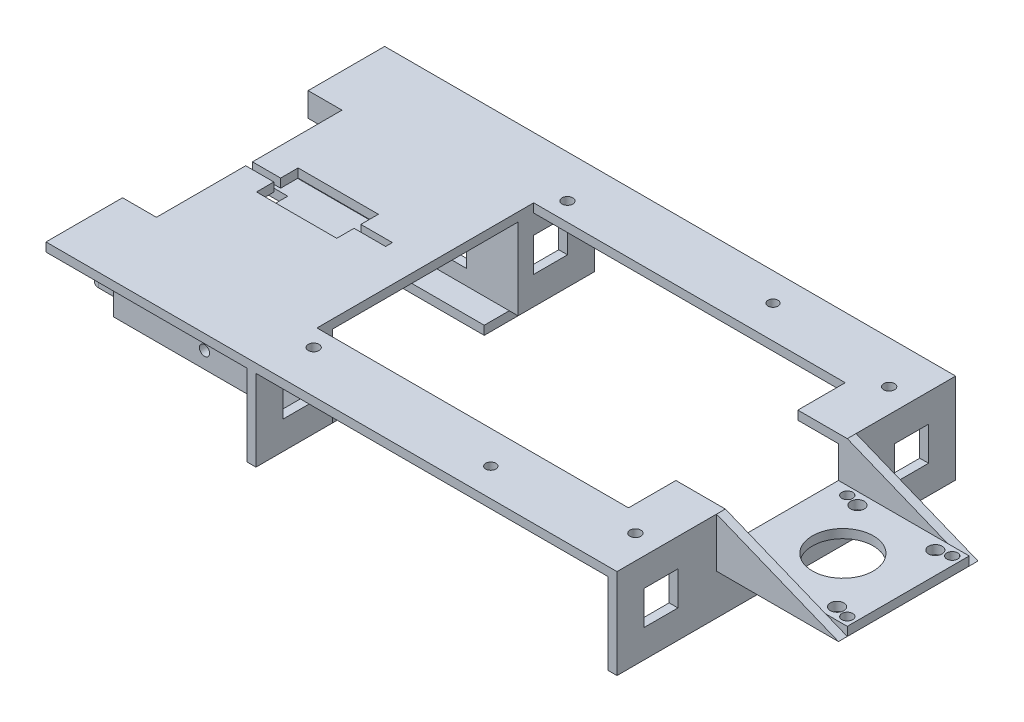
SolidWorks part; units mm, degrees
ref_plane "前视基准面" through (0, 0, 0) normal (0, 0, 1) x (1, 0, 0)
ref_plane "上视基准面" through (0, 0, 0) normal (0, 1, 0) x (1, 0, 0)
ref_plane "右视基准面" through (0, 0, 0) normal (1, 0, 0) x (0, 0, -1)
sketch "草图1" plane through (0, 0, 0) normal (0, 1, 0) x (1, 0, 0)
  line L0 (0, 0) -> (168.1938, 0) construction
  line L1 (0, 0) -> (0, 68.5187) construction
  line L2 (0, 50) -> (-52, 50)
  line L3 (-52, 50) -> (52, 50)
  line L5 (-52, -50) -> (52, -50)
  line L7 (0, 50) -> (52, 50)
  line L8 (52, 50) -> (52, -50)
  line L9 (-52, -50) -> (-52, 50)
  dimension "D1" = 100
  dimension "D3" = 52
  dimension "D4" = 52
extrude "凸台-拉伸1" add sketch "草图1" along normal blind 2.6 contours L9 L5 L8 L3 L2
ref_plane "基准面1" through (-52, 0, 0) normal (-1, 0, 0) x (0, 0, 1)
sketch "草图2" plane through (-52, 0, 0) normal (-1, 0, 0) x (0, 0, 1)
  line L0 (0, 0) -> (60.8879, 0) construction
  line L1 (0, 0) -> (0, 52.5684) construction
  line L4 (-50, 0) -> (50, 0)
  line L5 (-50, 0) -> (-50, 24)
  line L6 (-50, 24) -> (50, 24)
  line L7 (50, 0) -> (50, 24)
  dimension "D1" = 100
  dimension "D2" = 24
extrude "凸台-拉伸2" add sketch "草图2" along normal blind 2.6
ref_plane "基准面2" through (52, 0, 0) normal (1, 0, 0) x (0, 0, -1)
sketch "草图4" plane through (52, 0, 0) normal (1, 0, 0) x (0, 0, -1)
  line L0 (0, 0) -> (83.3328, 0) construction
  line L1 (0, 79.0959) -> (0, 0) construction
  line L3 (-50, 0) -> (50, 0)
  line L4 (-50, 0) -> (-50, 24)
  line L5 (-50, 24) -> (50, 24)
  line L6 (50, 0) -> (50, 24)
  dimension "D1" = 100
  dimension "D2" = 24
extrude "凸台-拉伸3" add sketch "草图4" along normal blind 2.6
ref_plane "基准面3" through (0, 24, 0) normal (0, 1, 0) x (1, 0, 0)
sketch "草图5" plane through (0, 24, 0) normal (0, 1, 0) x (1, 0, 0)
  line L0 (-54.6, 0) -> (-54.6, -62.7888) construction
  line L2 (-54.6, 0) -> (-103.1828, 0) construction
  line L3 (-52, 50) -> (-114, 50)
  line L4 (-52, 50) -> (-52, -50)
  line L5 (-52, -50) -> (-114, -50)
  line L6 (-114, 50) -> (-114, -50)
  dimension "D1" = 62
  dimension "D2" = 100
extrude "凸台-拉伸5" add sketch "草图5" along normal blind 2.6
ref_plane "基准面4" through (0, 24, 0) normal (0, 1, 0) x (1, 0, 0)
sketch "草图7" plane through (0, 24, 0) normal (0, 1, 0) x (1, 0, 0)
  line L0 (54.6, 0) -> (137.447, 0) construction
  line L2 (54.6, 0) -> (54.6, 43.4871) construction
  line L4 (52, -50) -> (114, -50)
  line L5 (52, -50) -> (52, 50)
  line L6 (52, 50) -> (114, 50)
  line L7 (114, -50) -> (114, 50)
  dimension "D1" = 62
  dimension "D2" = 100
extrude "凸台-拉伸6" add sketch "草图7" along normal blind 2.6
sketch "草图8" plane through (0, 24, 0) normal (0, 1, 0) x (1, 0, 0)
  line L13 (-54.6, 50) -> (-114, 50) construction
  line L14 (-114, 30) -> (-54.6, 30)
  line L15 (-114, 30) -> (-114, -30)
  line L16 (-114, -30) -> (-54.6, -30)
  line L17 (-54.6, 30) -> (-54.6, -30)
  line L18 (-114, -50) -> (-54.6, -50) construction
  line L19 (-54.6, -50) -> (-54.6, 50) construction
  line L20 (-114, 50) -> (-114, -50) construction
  dimension "D1" = 20
  dimension "D2" = 20
  dimension "D3" = 0
  dimension "D4" = 0
extrude "切除-拉伸1" cut sketch "草图8" along normal blind 2.6
sketch "草图9" plane through (0, 24, 0) normal (0, -1, 0) x (1, 0, 0)
  line L0 (54.6, 50) -> (114, 50) construction
  line L1 (54.6, 30) -> (114, 30)
  line L2 (54.6, 30) -> (54.6, -30)
  line L3 (54.6, -30) -> (114, -30)
  line L4 (114, 30) -> (114, -30)
  line L5 (114, -50) -> (54.6, -50) construction
  line L6 (54.6, -50) -> (54.6, 50) construction
  line L7 (114, 50) -> (114, -50) construction
  dimension "D1" = 20
  dimension "D2" = 20
  dimension "D3" = 0
  dimension "D4" = 0
extrude "切除-拉伸2" cut sketch "草图9" against normal blind 2.6
ref_plane "基准面6" through (0, 0, 30) normal (0, 0, -1) x (-1, 0, 0)
sketch "草图11" plane through (0, 0, 30) normal (0, 0, -1) x (-1, 0, 0)
  line L2 (-114, 26.6) -> (-54.6, 26.6)
  line L3 (-114, 26.6) -> (-114, 0)
  line L4 (-114, 0) -> (-54.6, 0)
  line L5 (-54.6, 26.6) -> (-54.6, 0)
extrude "凸台-拉伸7" add sketch "草图11" along normal blind 2.6
ref_plane "基准面7" through (0, 0, -30) normal (0, 0, 1) x (1, 0, 0)
sketch "草图12" plane through (0, 0, -30) normal (0, 0, 1) x (1, 0, 0)
  line L2 (54.6, 26.6) -> (114, 26.6)
  line L3 (54.6, 26.6) -> (54.6, 0)
  line L4 (54.6, 0) -> (114, 0)
  line L5 (114, 26.6) -> (114, 0)
extrude "凸台-拉伸8" add sketch "草图12" along normal blind 2.6
ref_plane "基准面8" through (0, 0, -30) normal (0, 0, 1) x (1, 0, 0)
sketch "草图14" plane through (0, 0, -30) normal (0, 0, 1) x (1, 0, 0)
  line L1 (-54.6, 26.6) -> (-114, 26.6)
  line L2 (-54.6, 26.6) -> (-54.6, 0)
  line L3 (-54.6, 0) -> (-114, 0)
  line L4 (-114, 26.6) -> (-114, 0)
extrude "凸台-拉伸9" add sketch "草图14" along normal blind 2.6
ref_plane "基准面9" through (0, 0, 30) normal (0, 0, -1) x (-1, 0, 0)
sketch "草图15" plane through (0, 0, 30) normal (0, 0, -1) x (-1, 0, 0)
  line L2 (54.6, 26.6) -> (114, 26.6)
  line L3 (54.6, 26.6) -> (54.6, 0)
  line L4 (54.6, 0) -> (114, 0)
  line L5 (114, 26.6) -> (114, 0)
extrude "凸台-拉伸10" add sketch "草图15" along normal blind 2.6
sketch "草图16" plane through (0, 2.6, 0) normal (0, 1, 0) x (1, 0, 0)
  line L0 (0, 0) -> (88.5453, 0) construction
  line L1 (0, 0) -> (0, 69.8905) construction
  circle A0 centre (-47.5, 37.465) radius 1.6
  circle A4 centre (47.5, 37.465) radius 1.6
  circle A5 centre (-47.5, -37.465) radius 1.6
  circle A6 centre (47.5, -37.465) radius 1.6
  dimension "D1" = 3.2
  dimension "D2" = 47.5
  dimension "D3" = 37.465
extrude "切除-拉伸3" cut sketch "草图16" against normal through all
sketch "草图17" plane through (0, 2.6, 0) normal (0, 1, 0) x (1, 0, 0)
  line L0 (0, 0) -> (0, -106.8297) construction
  line L1 (-40, 32) -> (40, 32)
  line L2 (-40, 32) -> (-40, -32)
  line L3 (-40, -32) -> (40, -32)
  line L4 (40, 32) -> (40, -32)
  line L5 (0, 0) -> (46.3374, 0) construction
  dimension "D1" = 80
  dimension "D2" = 64
extrude "切除-拉伸4" cut sketch "草图17" against normal through all contours L2 L1 L4 L3
sketch "草图19" plane through (0, 26.6, 0) normal (0, 1, 0) x (1, 0, 0)
sketch "草图21" plane through (0, 0, 0) normal (0, -1, 0) x (1, 0, 0)
  line L1 (-54.6, 27.4) -> (-114, 27.4)
  line L2 (-54.6, 27.4) -> (-54.6, -27.4)
  line L3 (-54.6, -27.4) -> (-114, -27.4)
  line L4 (-114, 27.4) -> (-114, -27.4)
extrude "凸台-拉伸11" add sketch "草图21" against normal blind 2.6
sketch "草图22" plane through (0, 2.6, 0) normal (0, 1, 0) x (1, 0, 0)
  line L0 (-114, -27.4) -> (-114, 27.4) construction
  line L1 (-114, 0) -> (-47.7388, 0) construction
  circle A0 centre (-109, 18) radius 1.6
  circle A1 centre (-109, 0) radius 1.6
  circle A2 centre (-109, -18) radius 1.6
  dimension "D1" = 3.2
  dimension "D3" = 3.2
  dimension "D2" = 5
  dimension "D4" = 18
extrude "切除-拉伸5" cut sketch "草图22" against normal blind 2.6
sketch "草图23" plane through (0, 26.6, 0) normal (0, 1, 0) x (1, 0, 0)
  line L1 (-114, 27.4) -> (-54.6, 27.4)
  line L2 (-114, 27.4) -> (-114, -27.4)
  line L3 (-114, -27.4) -> (-54.6, -27.4)
  line L4 (-54.6, 27.4) -> (-54.6, -27.4)
extrude "凸台-拉伸13" add sketch "草图23" against normal blind 2.6
sketch "草图24" plane through (0, 26.6, 0) normal (0, 1, 0) x (1, 0, 0)
  line L2 (-114, 0) -> (-114, 69.485) construction
  line L3 (-114, 27.4) -> (-104, 27.4)
  line L4 (-114, 27.4) -> (-114, -27.4)
  line L5 (-114, -27.4) -> (-104, -27.4)
  line L6 (-104, 27.4) -> (-104, 0.9702)
  line L7 (-94.7, 6.15) -> (-72, 6.15)
  line L8 (-94.7, 6.15) -> (-94.7, 0.9702)
  line L9 (-94.7, -6.15) -> (-72, -6.15)
  line L10 (-72, 6.15) -> (-72, 0.9702)
  line L11 (-52, -50) -> (-52, 50) construction
  line L12 (-104, -1.0298) -> (-104, -27.4)
  line L13 (-104, 0.9702) -> (-94.7, 0.9702)
  line L15 (-104, -1.0298) -> (-94.7, -1.0298)
  line L17 (-72, 0.9702) -> (-62.7, 0.9702)
  line L19 (-72, -1.0298) -> (-62.7, -1.0298)
  line L20 (-62.7, 0.9702) -> (-62.7, -1.0298)
  line L21 (-94.7, -1.0298) -> (-94.7, -6.15)
  line L22 (-72, -1.0298) -> (-72, -6.15)
  line L23 (-62.7, 0) -> (11.6044, 0) construction
  dimension "D1" = 54.8
  dimension "D2" = 0
  dimension "D4" = 22.7
  dimension "D5" = 12.3
  dimension "D6" = 20
  dimension "D7" = 2
  dimension "D8" = 9.3
  dimension "D9" = 9.3
extrude "切除-拉伸8" cut sketch "草图24" against normal blind 2.6 contours L7 L10 L17 L20 L19 L22 L9 L21 L15 L12 L5 L4 L3 L6 L13 L8
sketch "草图25" plane through (-54.6, 0, 0) normal (-1, 0, 0) x (0, 0, 1)
  line L2 (-27.4, 24) -> (27.4, 24)
  line L3 (-27.4, 24) -> (-27.4, 2.6)
  line L4 (-27.4, 2.6) -> (27.4, 2.6)
  line L5 (27.4, 24) -> (27.4, 2.6)
extrude "切除-拉伸9" cut sketch "草图25" against normal blind 2.6
sketch "草图28" plane through (0, 0, 30) normal (0, 0, 1) x (1, 0, 0)
  line L0 (-54.6, 24) -> (-54.6, 0) construction
  line L1 (-54.6, 12) -> (-123.8904, 12) construction
  circle A0 centre (-87.2, 20.75) radius 1.5
  circle A1 centre (-87.2, 3.25) radius 1.5
  dimension "D1" = 3
  dimension "D2" = 32.6
  dimension "D3" = 17.5
extrude "切除-拉伸11" cut sketch "草图28" against normal up to surface and the other way through all up to face at (-84.3, 12, -30)
sketch "草图31" plane through (0, 2.6, 0) normal (0, 1, 0) x (1, 0, 0)
  line L0 (-88.5519, -27.4) -> (-114, -27.4) construction
  line L1 (-52, 27.4) -> (-93.9958, 27.4)
  line L2 (-52, 27.4) -> (-52, -27.4)
  line L3 (-52, -27.4) -> (-93.9958, -27.4)
  line L4 (-93.9958, 27.4) -> (-93.9958, -27.4)
extrude "切除-拉伸14" cut sketch "草图31" against normal blind 2.6
sketch "草图32" plane through (0, 0, 30) normal (0, 0, 1) x (1, 0, 0)
  line L1 (54.6, 24) -> (114, 24)
  line L2 (54.6, 24) -> (54.6, 0)
  line L3 (54.6, 0) -> (114, 0)
  line L4 (114, 24) -> (114, 0)
extrude "切除-拉伸15" cut sketch "草图32" against normal blind 70.6
sketch "草图33" plane through (0, 2.6, 0) normal (0, 1, 0) x (1, 0, 0)
  line L1 (-52, 50) -> (52, 50)
  line L2 (-52, 50) -> (-52, -50)
  line L3 (-52, -50) -> (52, -50)
  line L4 (52, 50) -> (52, -50)
extrude "切除-拉伸16" cut sketch "草图33" against normal blind 2.6
sketch "草图34" plane through (0, 0, 0) normal (0, -1, 0) x (1, 0, 0)
  line L0 (52, 50) -> (52, -50) construction
  line L1 (-52, 50) -> (52, 50)
  line L2 (-52, 50) -> (-52, -49.6726)
  line L3 (-52, -49.6726) -> (52, -49.6726)
  line L4 (52, 50) -> (52, -49.6726)
extrude "凸台-拉伸14" add sketch "草图34" against normal blind 2.6
sketch "草图35" plane through (0, 2.6, 0) normal (0, 1, 0) x (1, 0, 0)
  line L0 (0, 0) -> (174.9155, 0) construction
  line L1 (0, 0) -> (0, 73.4475) construction
  line L4 (-42, 24) -> (12, 24) construction
  line L5 (-42, 24) -> (-42, -24) construction
  line L6 (-42, -24) -> (12, -24) construction
  line L7 (12, 24) -> (12, -24) construction
  line L8 (-52, 27.4) -> (-52, 49.6726) construction
  circle A0 centre (-39.5, 21.5) radius 1.6
  circle A2 centre (9.5, 21.5) radius 1.6
  circle A3 centre (9.5, -21.5) radius 1.6
  circle A4 centre (-39.5, -21.5) radius 1.6
  dimension "D4" = 3.2
  dimension "D5" = 2.5
  dimension "D6" = 2.5
  dimension "D7" = 3.2
  dimension "D8" = 2.5
  dimension "D9" = 2.5
  dimension "D1" = 54
  dimension "D2" = 48
  dimension "D3" = 10
extrude "切除-拉伸24" cut sketch "草图35" against normal blind 2.6
sketch "草图36" plane through (0, 26.6, 0) normal (0, 1, 0) x (1, 0, 0)
  line L0 (52, -50) -> (114, -50) construction
  line L1 (114, 50) -> (54.6, 50)
  line L2 (114, 50) -> (114, -50)
  line L3 (114, -50) -> (54.6, -50)
  line L4 (54.6, 50) -> (54.6, -50)
extrude "切除-拉伸25" cut sketch "草图36" against normal blind 2.6
sketch "草图37" plane through (54.6, 0, 0) normal (1, 0, 0) x (0, 0, -1)
  line L0 (0, 0) -> (0, 48.9545) construction
  line L1 (-50, 0) -> (50, 0) construction
  line L2 (50, 13.3) -> (-60.8276, 13.3) construction
  line L4 (-18, 14.6) -> (18, 14.6)
  line L5 (-18, 14.6) -> (-18, 12)
  line L6 (-18, 12) -> (18, 12)
  line L7 (18, 14.6) -> (18, 12)
  dimension "D1" = 2.6
  dimension "D2" = 36
  dimension "D3" = 12
extrude "凸台-拉伸17" add sketch "草图37" along normal blind 36
sketch "草图41" plane through (54.6, 0, 0) normal (1, 0, 0) x (0, 0, -1)
  line L0 (-50, 26.6) -> (50, 26.6) construction
  line L1 (-18, 14.6) -> (18, 14.6)
  line L2 (-18, 14.6) -> (-18, 26.6)
  line L3 (-18, 26.6) -> (18, 26.6)
  line L4 (18, 14.6) -> (18, 26.6)
  dimension "D1" = 36
extrude "切除-拉伸27" cut sketch "草图41" against normal blind 2.6
sketch "草图42" plane through (0, 14.6, 0) normal (0, 1, 0) x (1, 0, 0)
  line L0 (90.6, 18) -> (54.6, 18) construction
  line L4 (90.6, 18) -> (90.6, -18) construction
  line L5 (90.6, 0) -> (52, 0) construction
  circle A0 centre (88.1, 15.5) radius 1.6
  circle A1 centre (88.1, -15.5) radius 1.6
  circle A2 centre (57.1, 15.5) radius 1.6
  circle A3 centre (57.1, -15.5) radius 1.6
  dimension "D1" = 3.2
  dimension "D2" = 2.5
  dimension "D3" = 2.5
  dimension "D4" = 2
extrude "切除-拉伸28" cut sketch "草图42" against normal blind 2.6
sketch "草图43" plane through (0, 14.6, 0) normal (0, 1, 0) x (1, 0, 0)
  line L0 (90.6, 0) -> (48.4873, 0) construction
  line L1 (90.6, 18) -> (90.6, -18) construction
  line L2 (57.1, 15.5) -> (88.1, 15.5)
  line L3 (72.6, 15.5) -> (72.6, -18) construction
  line L4 (90.6, -18) -> (54.6, -18) construction
  circle A0 centre (61.1, 14.5) radius 2
  circle A1 centre (84.1, 14.5) radius 2
  circle A2 centre (84.1, -14.5) radius 2
  circle A3 centre (61.1, -14.5) radius 2
  dimension "D1" = 4
  dimension "D3" = 11.5
  dimension "D4" = 14.5
extrude "切除-拉伸29" cut sketch "草图43" against normal blind 2.6 contours A0 | A1 | A3 | A2
sketch "草图44" plane through (0, 26.6, 0) normal (0, 1, 0) x (1, 0, 0)
  line L1 (-52, 49.6726) -> (52, 49.6726)
  line L2 (-52, 49.6726) -> (-52, -50)
  line L3 (-52, -50) -> (52, -50)
  line L4 (52, 49.6726) -> (52, -50)
extrude "凸台-拉伸18" add sketch "草图44" against normal blind 2.6
sketch "草图45" plane through (0, 26.6, 0) normal (0, 1, 0) x (1, 0, 0)
  line L0 (-61.404, 0) -> (112.1459, 0) construction
  line L1 (-50, 40) -> (50, 40) construction
  line L2 (-50, 40) -> (-50, -40) construction
  line L3 (-50, -40) -> (50, -40) construction
  line L4 (50, 40) -> (50, -40) construction
  line L5 (0, 0) -> (0, 74.2403) construction
  circle A0 centre (-47.5, -37.465) radius 1.6
  circle A1 centre (-47.5, 37.465) radius 1.6
  circle A2 centre (47.5, -37.465) radius 1.6
  circle A3 centre (47.5, 37.465) radius 1.6
  dimension "D1" = 3.2
  dimension "D2" = 2.535
  dimension "D3" = 2.5
extrude "切除-拉伸30" cut sketch "草图45" against normal blind 2.6
sketch "草图46" plane through (0, 26.6, 0) normal (0, 1, 0) x (1, 0, 0)
  line L0 (0, 0) -> (106.198, 0) construction
  line L1 (-40, 32) -> (40, 32)
  line L2 (-40, 32) -> (-40, -32)
  line L3 (-40, -32) -> (40, -32)
  line L4 (40, 32) -> (40, -32)
  line L5 (0, 0) -> (0, 58.9714) construction
  dimension "D1" = 80
  dimension "D2" = 64
extrude "切除-拉伸31" cut sketch "草图46" against normal blind 2.6 contours L2 L1 L4 L3
sketch "草图47" plane through (0, 2.6, 0) normal (0, 1, 0) x (1, 0, 0)
  line L0 (-40, 0) -> (22.2042, 0) construction
  line L3 (-15, 21.5) -> (-15, -18.6922) construction
  line L4 (-35, 15) -> (5, 15)
  line L5 (-35, 15) -> (-35, -15)
  line L6 (-35, -15) -> (5, -15)
  line L7 (5, 15) -> (5, -15)
  dimension "D1" = 40
  dimension "D2" = 30
extrude "切除-拉伸32" cut sketch "草图47" against normal blind 2.6 contours L5 L4 L7 L6
sketch "草图48" plane through (0, 26.6, 0) normal (0, 1, 0) x (1, 0, 0)
  line L1 (-40, 32) -> (-52, 32)
  line L2 (-40, 32) -> (-40, -32)
  line L3 (-40, -32) -> (-52, -32)
  line L4 (-52, 32) -> (-52, -32)
  dimension "D1" = 12
extrude "切除-拉伸33" cut sketch "草图48" against normal blind 2.6
sketch "草图49" plane through (0, 2.6, 0) normal (0, 1, 0) x (1, 0, 0)
  line L6 (-35, 15) -> (5, 15)
  line L7 (-35, 15) -> (-35, 35.5471)
  line L8 (-35, 35.5471) -> (5, 35.5471)
  line L9 (5, 15) -> (5, 35.5471)
  line L10 (-35, -15) -> (5, -15)
  line L11 (-35, -15) -> (-35, -35)
  line L12 (-35, -35) -> (5, -35)
  line L13 (5, -15) -> (5, -35)
  dimension "D1" = 20
extrude "切除-拉伸34" cut sketch "草图49" against normal blind 2.6 contours L11 L10 L13 L12
sketch "草图50" plane through (0, 2.6, 0) normal (0, 1, 0) x (1, 0, 0)
  line L1 (-35, 15) -> (4.9378, 15)
  line L2 (-35, 15) -> (-35, 35)
  line L3 (-35, 35) -> (4.9378, 35)
  line L4 (4.9378, 15) -> (4.9378, 35)
  dimension "D1" = 20
extrude "切除-拉伸35" cut sketch "草图50" against normal blind 2.6
sketch "草图51" plane through (0, 14.6, 0) normal (0, 1, 0) x (1, 0, 0)
  line L4 (52, 18) -> (90.6, -18) construction
  line L6 (90.6, 18) -> (52, -18) construction
  circle A1 centre (71.3, 0) radius 9
  dimension "D1" = 18
extrude "切除-拉伸36" cut sketch "草图51" against normal blind 2.6
sketch "草图52" plane through (0, 0, 30) normal (0, 0, 1) x (1, 0, 0)
  line L0 (-87.2, 20.75) -> (-87.2, 3.25) construction
  line L1 (-87.2, 12) -> (-58.053, 12) construction
  line L2 (-67.2, 4.5) -> (-82.2, 4.5)
  line L3 (-107.2, 19.5) -> (-92.2, 19.5)
  line L4 (-107.2, 19.5) -> (-107.2, 4.5)
  line L5 (-107.2, 4.5) -> (-92.2, 4.5)
  line L6 (-92.2, 19.5) -> (-92.2, 4.5)
  line L7 (-82.2, 19.5) -> (-82.2, 4.5)
  line L8 (-67.2, 19.5) -> (-82.2, 19.5)
  line L9 (-67.2, 19.5) -> (-67.2, 4.5)
  dimension "D1" = 15
  dimension "D2" = 15
  dimension "D3" = 5
extrude "切除-拉伸38" cut sketch "草图52" against normal up to surface (60 mm away) up to face at (-88.7, 20.75, -30)
sketch "草图55" plane through (52, 0, 0) normal (1, 0, 0) x (0, 0, -1)
  line L1 (-18, 26.6) -> (18, 26.6)
  line L2 (-18, 26.6) -> (-18, 24)
  line L3 (-18, 24) -> (18, 24)
  line L4 (18, 26.6) -> (18, 24)
extrude "切除-拉伸39" cut sketch "草图55" against normal up to surface (12 mm away) up to face at (40, 25.3, 0)
sketch "草图56" plane through (54.6, 0, 0) normal (1, 0, 0) x (0, 0, -1)
  line L0 (-50, 13.3) -> (50, 13.3) construction
  line L3 (0, 0) -> (0, 44.005) construction
  line L5 (-50, 26.6) -> (-50, 0) construction
  line L6 (-42, 18.3) -> (-32, 18.3)
  line L7 (-42, 18.3) -> (-42, 8.3)
  line L8 (-42, 8.3) -> (-32, 8.3)
  line L9 (-32, 18.3) -> (-32, 8.3)
  line L10 (42, 8.3) -> (32, 8.3)
  line L11 (32, 18.3) -> (32, 8.3)
  line L12 (42, 18.3) -> (32, 18.3)
  line L13 (42, 18.3) -> (42, 8.3)
  dimension "D1" = 10
  dimension "D2" = 10
  dimension "D3" = 8
extrude "切除-拉伸40" cut sketch "草图56" against normal up to surface (109.2 mm away)
sketch "草图57" plane through (0, 0, 0) normal (0, -1, 0) x (1, 0, 0)
  line L0 (0, 0) -> (134.0882, 0) construction
  line L1 (0, 0) -> (0, 78.3548) construction
  line L2 (-52, -49.6726) -> (52, -49.6726) construction
  circle A0 centre (9, -41.6726) radius 1.5
  circle A1 centre (9, 41.6726) radius 1.5
  dimension "D1" = 3
  dimension "D3" = 9
  dimension "D2" = 8
extrude "切除-拉伸41" cut sketch "草图57" against normal up to surface (26.6 mm away) up to face at (-47.5, 26.6, -39.065)
sketch "草图58" plane through (0, 0, -49.6726) normal (0, 0, -1) x (-1, 0, 0)
  line L0 (-52, 24) -> (-52, 26.6) construction
  line L1 (52, 2.6) -> (-52, 2.6)
  line L2 (52, 2.6) -> (52, 0)
  line L3 (52, 0) -> (-52, 0)
  line L4 (-52, 2.6) -> (-52, 0)
  line L5 (-52, 26.6) -> (52, 26.6)
  line L6 (-52, 26.6) -> (-52, 24)
  line L7 (-52, 24) -> (52, 24)
  line L8 (52, 26.6) -> (52, 24)
extrude "凸台-拉伸19" add sketch "草图58" along normal up to surface (0.3274 mm away) contours L8 L5 L6 L7 | L2 L1 L4 L3 up to face at (-73.5333, 16.8667, -50)
sketch "草图59" plane through (0, 0, 0) normal (0, -1, 0) x (1, 0, 0)
  line L1 (-54.6, 50) -> (54.6, 50)
  line L2 (-54.6, 50) -> (-54.6, -50)
  line L3 (-54.6, -50) -> (54.6, -50)
  line L4 (54.6, 50) -> (54.6, -50)
extrude "切除-拉伸42" cut sketch "草图59" against normal blind 2.6
sketch "草图60" plane through (0, 0, -30) normal (0, 0, -1) x (-1, 0, 0)
  line L0 (114, 24) -> (114, 0) construction
  line L1 (107.2, 19.5) -> (114, 19.5)
  line L2 (107.2, 19.5) -> (107.2, 4.5)
  line L3 (107.2, 4.5) -> (114, 4.5)
  line L4 (114, 19.5) -> (114, 4.5)
extrude "切除-拉伸43" cut sketch "草图60" against normal blind 1000
sketch "草图61" plane through (0, 0, -18) normal (0, 0, -1) x (-1, 0, 0)
  line L0 (-54.6, 12) -> (-90.6, 12)
  line L1 (-90.6, 12) -> (-54.6, 26.6)
  line L2 (-54.6, 26.6) -> (-54.6, 12)
extrude "凸台-拉伸20" add sketch "草图61" along normal blind 2.6
sketch "草图62" plane through (0, 0, 18) normal (0, 0, 1) x (1, 0, 0)
  line L1 (54.6, 26.6) -> (54.6, 12)
  line L2 (54.6, 12) -> (90.6, 12)
  line L3 (90.6, 12) -> (54.6, 26.6)
extrude "凸台-拉伸21" add sketch "草图62" along normal blind 2.6 contours L3 L1 L2
sketch "草图63" plane through (0, 2.6, 0) normal (0, 1, 0) x (1, 0, 0)
  circle A0 centre (-109, 18) radius 1.6
  circle A1 centre (-109, 0) radius 1.6
  circle A2 centre (-109, -18) radius 1.6
extrude "凸台-拉伸22" add sketch "草图63" against normal blind 2.6
sketch "草图64" plane through (0, 2.6, 0) normal (0, 1, 0) x (1, 0, 0)
  line L0 (-93.9958, 0) -> (-124, 0) construction
  line L1 (-114, 27.4) -> (-121, 27.4)
  line L2 (-114, 27.4) -> (-114, 21.4)
  line L3 (-114, -27.3981) -> (-121.108, -27.3981)
  line L5 (-93.9958, 27.4) -> (-93.9958, -27.4) construction
  line L6 (-131.8735, 0) -> (-131.8735, 33.1796) construction
  line L7 (-121, -3) -> (-114, -3)
  line L8 (-121, 21.4) -> (-114, 21.4)
  line L10 (-121, 3) -> (-114, 3)
  line L13 (-121, -21.4) -> (-114, -21.4)
  line L16 (-114, 3) -> (-114, -3)
  line L17 (-114, -21.4) -> (-114, -27.3981)
  circle A0 centre (-121, 0) radius 1.6
  circle A1 centre (-121, 24.4) radius 1.6
  circle A2 centre (-121, -24.4) radius 1.6
  arc A3 (-121, 27.4) -> (-121, 21.4) centre (-121, 24.4) ccw
  arc A4 (-121, 3) -> (-121, -3) centre (-121, 0) ccw
  arc A5 (-121, -21.4) -> (-120.892, -27.3981) centre (-121, -24.4) ccw
  line M19 (-114, 27.4) -> (-114, -27.4)
  dimension "D2" = 3.2
  dimension "D4" = 3.2
  dimension "D6" = 3
  dimension "D8" = 3
  dimension "D9" = 3
extrude "凸台-拉伸23" add sketch "草图64" against normal blind 2.6 contours L1 A3 L8 A1 M19 | L10 A4 L7 A0 M19 | L13 A5 L3 A2 M19
sketch "草图65" plane through (0, 26.6, 0) normal (0, 1, 0) x (1, 0, 0)
  line L1 (-94.7, 6.15) -> (-95.7, 6.15)
  line L2 (-94.7, 6.15) -> (-94.7, -6.1414)
  line L3 (-94.7, -6.1414) -> (-95.7, -6.1414)
  line L4 (-95.7, 6.15) -> (-95.7, -6.1414)
  dimension "D1" = 1
extrude "切除-拉伸44" cut sketch "草图65" against normal blind 2.6
sketch "草图66" plane through (0, 2.6, 0) normal (0, -1, 0) x (1, 0, 0)
  line L1 (-54.6, 50) -> (-52, 50)
  line L2 (-54.6, 50) -> (-54.6, 27.4)
  line L3 (-54.6, 27.4) -> (-52, 27.4)
  line L4 (-52, 50) -> (-52, 27.4)
  line L5 (-54.6, -27.4) -> (-52, -27.4)
  line L6 (-54.6, -27.4) -> (-54.6, -50)
  line L7 (-54.6, -50) -> (-52, -50)
  line L8 (-52, -27.4) -> (-52, -50)
  line L9 (52, -50) -> (54.6, -50)
  line L10 (52, -50) -> (52, 50)
  line L11 (52, 50) -> (54.6, 50)
  line L12 (54.6, -50) -> (54.6, 50)
extrude "凸台-拉伸24" add sketch "草图66" along normal blind 2.6
sketch "草图68" plane through (0, 0, 0) normal (0, -1, 0) x (1, 0, 0)
  line L1 (-54.6, 30) -> (-114, 30)
  line L2 (-54.6, 30) -> (-54.6, 27.3981)
  line L3 (-54.6, 27.3981) -> (-114, 27.3981)
  line L4 (-114, 30) -> (-114, 27.3981)
  line L5 (-54.6, -30) -> (-114, -30)
  line L6 (-54.6, -30) -> (-54.6, -27.4)
  line L7 (-54.6, -27.4) -> (-114, -27.4)
  line L8 (-114, -30) -> (-114, -27.4)
extrude "凸台-拉伸26" add sketch "草图68" along normal blind 2.6
sketch "草图69" plane through (0, 0, 30) normal (0, 0, 1) x (1, 0, 0)
  circle A0 centre (-87.2, 3.25) radius 1.5
  circle A1 centre (-87.2, 20.75) radius 1.5
extrude "凸台-拉伸28" add sketch "草图69" against normal blind 2.6
sketch "草图70" plane through (0, 0, -30) normal (0, 0, -1) x (-1, 0, 0)
  line L0 (87.2, 20.75) -> (87.2, 2.6061) construction
  line L1 (54.6, 24) -> (114, 24) construction
  circle A0 centre (87.2, 19.75) radius 1.5
  circle A1 centre (87.2, 2.25) radius 1.5
  point P9 (87.2, 0.8802)
  dimension "D1" = 3
  dimension "D4" = 3
  dimension "D2" = 4.25
  dimension "D3" = 17.5
extrude "切除-拉伸45" cut sketch "草图70" against normal up to surface (60 mm away) up to face at (-89.3556, 10.0889, 30)
sketch "草图71" plane through (0, 0, -30) normal (0, 0, -1) x (-1, 0, 0)
  arc A0 (88.6142, 20.25) -> (85.7858, 20.25) centre (87.2, 20.75) ccw
  arc A1 (88.6142, 20.25) -> (85.7858, 20.25) centre (87.2, 19.75) ccw
  arc A2 (88.6142, 2.75) -> (85.7858, 2.75) centre (87.2, 2.25) ccw
  arc A3 (88.6142, 2.75) -> (85.7858, 2.75) centre (87.2, 3.25) ccw
extrude "凸台-拉伸29" add sketch "草图71" against normal blind 2.6
sketch "草图72" plane through (0, 0, 0) normal (0, -1, 0) x (1, 0, 0)
sketch "草图73" plane through (0, 0, 27.3981) normal (0, 0, -1) x (-1, 0, 0)
  line L1 (114, -2.6) -> (54.6, -2.6)
  line L2 (114, -2.6) -> (114, 0)
  line L3 (114, 0) -> (54.6, 0)
  line L4 (54.6, -2.6) -> (54.6, 0)
extrude "凸台-拉伸30" add sketch "草图73" along normal up to surface (54.7981 mm away)
sketch "草图74" plane through (0, -2.6, 0) normal (0, -1, 0) x (1, 0, 0)
  line L0 (-54.6, -30) -> (-54.6, 30) construction
  line L1 (-54.6, 20) -> (-93.9958, 20)
  line L2 (-54.6, 20) -> (-54.6, -20)
  line L3 (-54.6, -20) -> (-93.9958, -20)
  line L4 (-93.9958, 20) -> (-93.9958, -20)
  line L5 (-54.6, 30) -> (-114, 30) construction
  line L6 (-114, -30) -> (-54.6, -30) construction
  line L7 (-93.9958, -27.4) -> (-93.9958, 27.4) construction
  dimension "D1" = 10
  dimension "D2" = 10
  dimension "D3" = 0
extrude "切除-拉伸46" cut sketch "草图74" against normal blind 2.6 contours L2 L1 L4 L3
